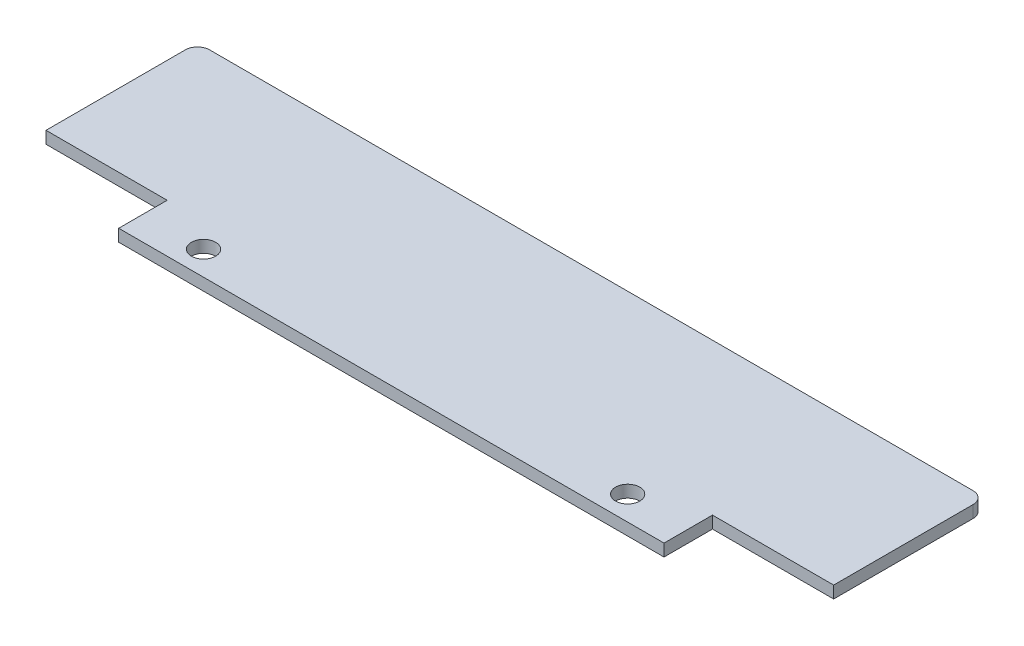
SolidWorks part; units mm, degrees
ref_plane "Front Plane" through (0, 0, 0) normal (0, 0, 1) x (1, 0, 0)
ref_plane "Top Plane" through (0, 0, 0) normal (0, 1, 0) x (1, 0, 0)
ref_plane "Right Plane" through (0, 0, 0) normal (1, 0, 0) x (0, 0, -1)
sketch "Sketch1" plane through (0, 0, 0) normal (0, 1, 0) x (1, 0, 0)
  line L0 (0, 0) -> (0, 10.5) construction
  line L2 (65, 12.5) -> (65, -12.5)
  line L3 (65, -12.5) -> (45, -12.5)
  line L4 (-65, 12.5) -> (-65, -12.5)
  line L5 (65, 12.5) -> (-65, -12.5) construction
  line L6 (65, -12.5) -> (-65, 12.5) construction
  line L7 (-45, -12.5) -> (-45, -20.5)
  line L8 (-45, -20.5) -> (45, -20.5)
  line L9 (45, -20.5) -> (45, -12.5)
  line L10 (-45, -12.5) -> (-65, -12.5)
  line L11 (-65, 12.5) -> (65, 12.5)
  circle A0 centre (-35, -16.5) radius 2
  circle A1 centre (35, -16.5) radius 2
  point P0 (0, 0)
  dimension "D6" = 10
  dimension "D1" = 130
  dimension "D2" = 25
  dimension "D3" = 20
  dimension "D4" = 90
  dimension "D5" = 8
  dimension "D7" = 10
  dimension "D8" = 4
  dimension "D9" = 4
  dimension "D12" = 25
extrude "Boss-Extrude1" add sketch "Sketch1" along normal blind 2
fillet "Fillet1" radius 2 2 edges at (65, 1, -12.5) (-65, 1, -12.5)
